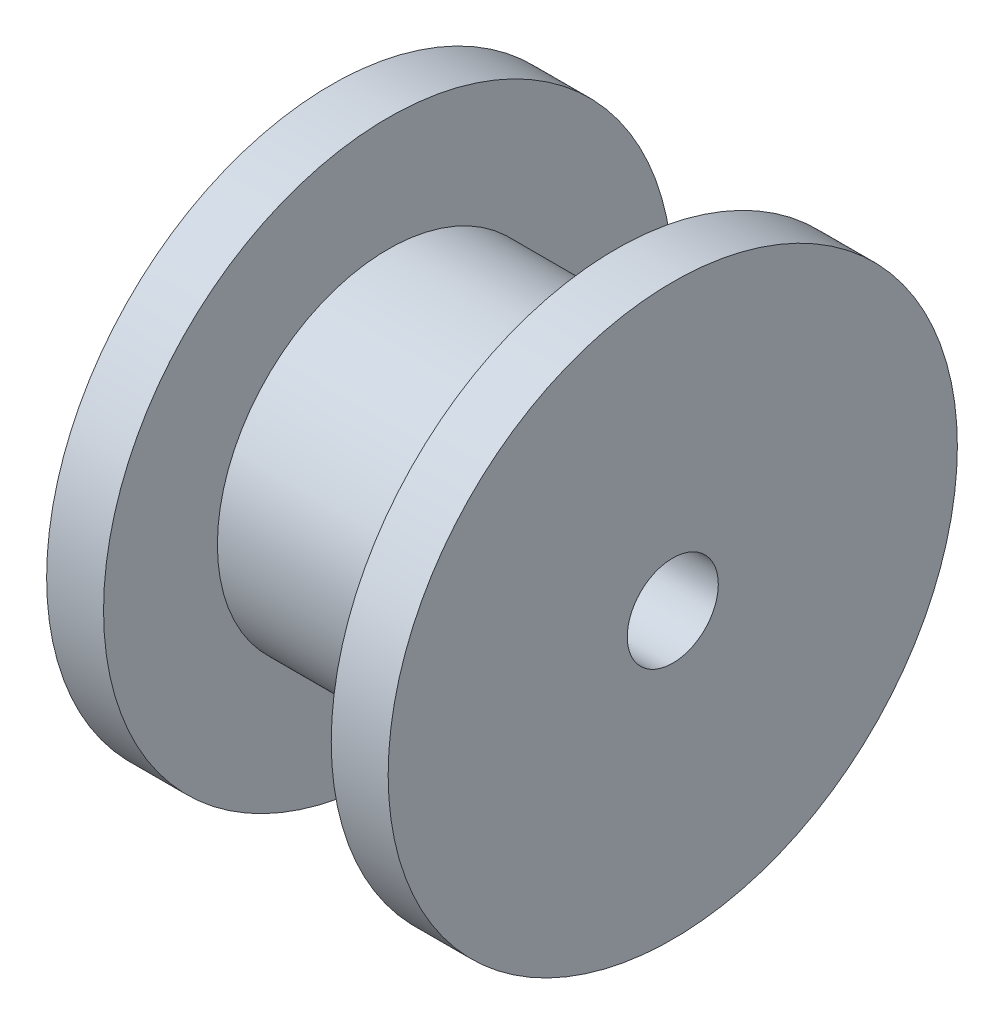
SolidWorks part; units mm, degrees
ref_plane "Спереди" through (0, 0, 0) normal (0, 0, 1) x (1, 0, 0)
ref_plane "Сверху" through (0, 0, 0) normal (0, 1, 0) x (1, 0, 0)
ref_plane "Справа" through (0, 0, 0) normal (1, 0, 0) x (0, 0, -1)
sketch "Эскиз1" plane through (0, 0, 0) normal (1, 0, 0) x (0, 0, -1)
  circle A1 centre (0, 0) radius 10
extrude "Бобышка-Вытянуть1" add sketch "Эскиз1" along normal blind 2
sketch "Эскиз2" plane through (2, 0, 0) normal (1, 0, 0) x (0, 0, -1)
  circle A0 centre (0, 0) radius 6
extrude "Бобышка-Вытянуть2" add sketch "Эскиз2" along normal blind 8
sketch "Эскиз3" plane through (10, 0, 0) normal (1, 0, 0) x (0, 0, -1)
  circle A0 centre (0, 0) radius 10
extrude "Бобышка-Вытянуть3" add sketch "Эскиз3" along normal blind 2
sketch "Эскиз6" plane through (12, 0, 0) normal (1, 0, 0) x (0, 0, -1)
  circle A0 centre (0, 0) radius 1.6
extrude "Вырез-Вытянуть3" cut sketch "Эскиз6" against normal through all
